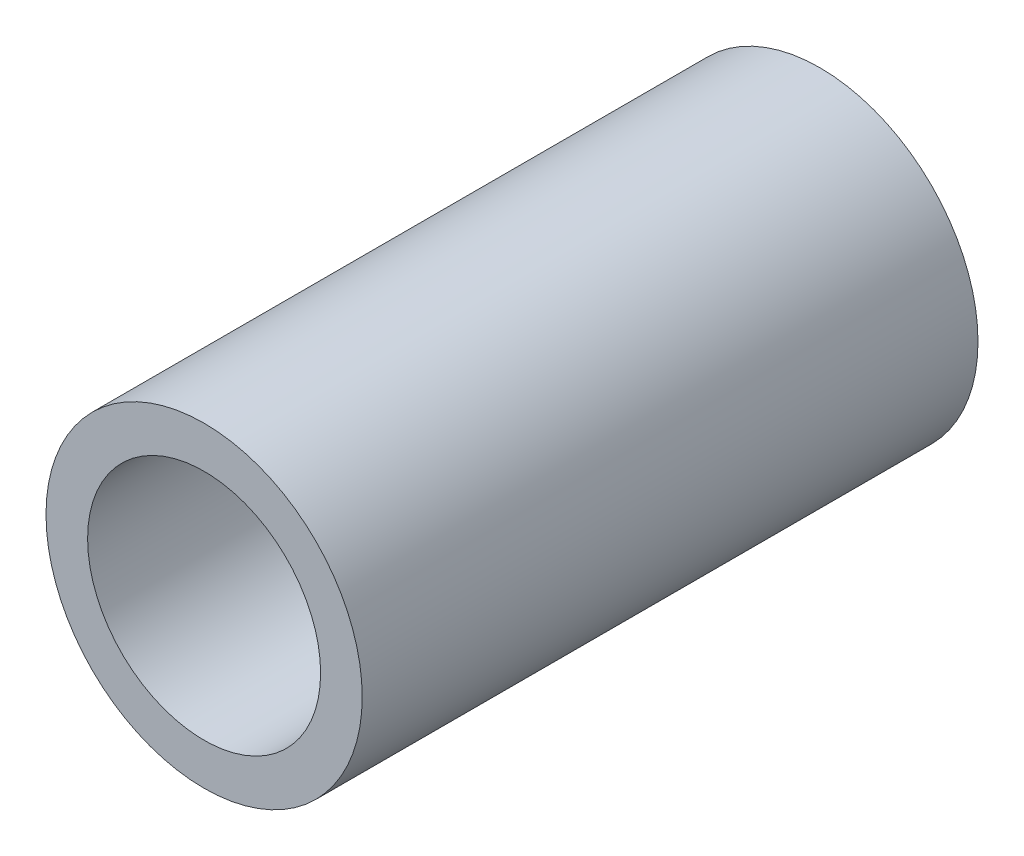
SolidWorks part; units mm, degrees
ref_plane "Ön Düzlem" through (0, 0, 0) normal (0, 0, 1) x (1, 0, 0)
ref_plane "Üst Düzlem" through (0, 0, 0) normal (0, 1, 0) x (1, 0, 0)
ref_plane "Sağ Düzlem" through (0, 0, 0) normal (1, 0, 0) x (0, 0, -1)
sketch "Sketch1" plane through (0, 0, 0) normal (0, 0, 1) x (1, 0, 0)
  circle A0 centre (0, 0) radius 7
  circle A1 centre (0, 0) radius 9.5
extrude "Boss-Extrude1" add sketch "Sketch1" along normal blind 37
